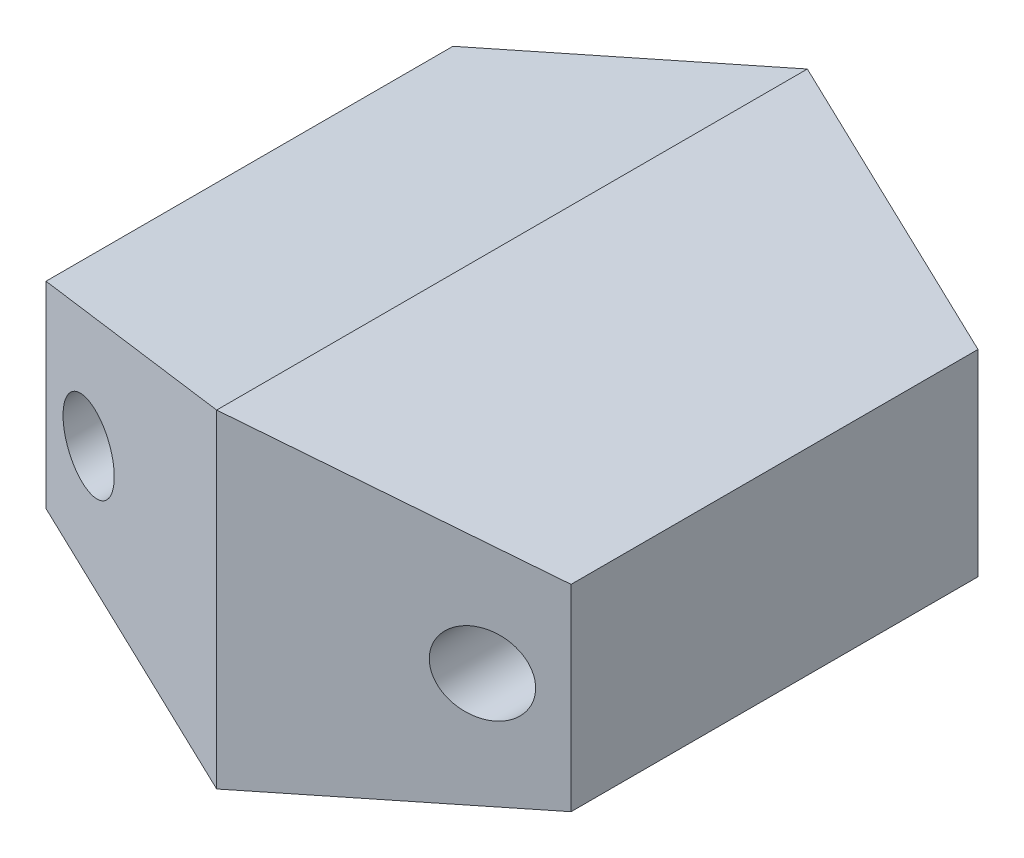
SolidWorks part; units mm, degrees
ref_plane "Front Plane" through (0, 0, 0) normal (0, 0, 1) x (1, 0, 0)
ref_plane "Top Plane" through (0, 0, 0) normal (0, 1, 0) x (1, 0, 0)
ref_plane "Right Plane" through (0, 0, 0) normal (1, 0, 0) x (0, 0, -1)
sketch "Sketch1" plane through (0, 0, 0) normal (0, 0, 1) x (1, 0, 0)
  line L1 (-20, -12.5) -> (20, -12.5)
  line L2 (-20, -12.5) -> (-20, 12.5)
  line L3 (-20, 12.5) -> (20, 12.5)
  line L4 (20, -12.5) -> (20, 12.5)
  line L5 (-20, -12.5) -> (20, 12.5) construction
  line L6 (-20, 12.5) -> (20, -12.5) construction
  point P0 (0, 0)
  dimension "D1" = 40
  dimension "D2" = 25
extrude "Boss-Extrude1" add sketch "Sketch1" along normal blind 45
sketch "Sketch2" plane through (0, 12.5, 0) normal (0, 1, 0) x (1, 0, 0)
  line L0 (0, 0) -> (0, 7.8489) construction
  line L1 (-20, -22.5) -> (21.3218, -22.5) construction
  line L2 (-20, -45) -> (-20, 0) construction
  line L3 (0, 0) -> (-20, -7)
  line L4 (20, 0) -> (-20, 0) construction
  line L5 (0, 0) -> (20, -7)
  line L6 (0, -45) -> (20, -38)
  line L7 (0, -45) -> (-20, -38)
  line L8 (-20, -7) -> (-20, 0)
  line L9 (-20, 0) -> (0, 0)
  line L10 (0, 0) -> (20, 0)
  line L11 (20, 0) -> (20, -7)
  line L12 (20, -38) -> (20, -45)
  line L13 (20, -45) -> (0, -45)
  line L14 (-20, -38) -> (-20, -45)
  line L15 (-20, -45) -> (0, -45)
  line M5 (20, 0) -> (-20, 0)
  line M6 (-20, 0) -> (-20, -45)
  line M7 (-20, -45) -> (20, -45)
  line M8 (20, -45) -> (20, 0)
  dimension "D1" = 7
extrude "Cut-Extrude1" cut sketch "Sketch2" against normal blind 45 contours L7 M7 M6 | L6 M7 M8 | L5 M5 M8 | L3 L8 L9
sketch "Sketch3" plane through (0, 0, 0) normal (0, 0, 1) x (1, 0, 0)
  line L0 (0, 12.5) -> (-20, 7.5)
  line L1 (-20, -12.5) -> (-20, 12.5) construction
  line L2 (0, 0) -> (0, 3.1642) construction
  line L3 (0, 12.5) -> (0, -12.5) construction
  line L4 (0, 0) -> (3.7012, 0) construction
  line L5 (0, 12.5) -> (-20, 12.5) construction
  line L6 (0, 12.5) -> (20, 7.5)
  line L7 (0, -12.5) -> (20, -7.5)
  line L8 (0, -12.5) -> (-20, -7.5)
  line L9 (-20, 7.5) -> (-20, 12.5)
  line L10 (-20, 12.5) -> (0, 12.5)
  line L11 (0, 12.5) -> (20, 12.5)
  line L12 (20, 12.5) -> (20, 7.5)
  line L13 (20, -7.5) -> (20, -12.5)
  line L14 (20, -12.5) -> (0, -12.5)
  line L15 (0, -12.5) -> (-20, -12.5)
  line L16 (0, -12.5) -> (-20, -12.5) construction
  line L17 (-20, -12.5) -> (-20, -7.5)
  dimension "D1" = 5
extrude "Cut-Extrude2" cut sketch "Sketch3" along normal blind 45 contours L10 L9 L0 | L12 L11 L6 | L14 L13 L7 | L17 L15 L8
sketch "Sketch4" plane through (0, 0, 0) normal (0, 0, 1) x (1, 0, 0)
  line L0 (0, 0) -> (0, 2.4355) construction
  line L1 (0, 12.5) -> (0, -12.5) construction
  line L2 (-20, -7.5) -> (-20, 7.5) construction
  circle A0 centre (-15, 0) radius 3
  circle A1 centre (15, 0) radius 3
  dimension "D1" = 5
extrude "Cut-Extrude3" cut sketch "Sketch4" along normal through all
